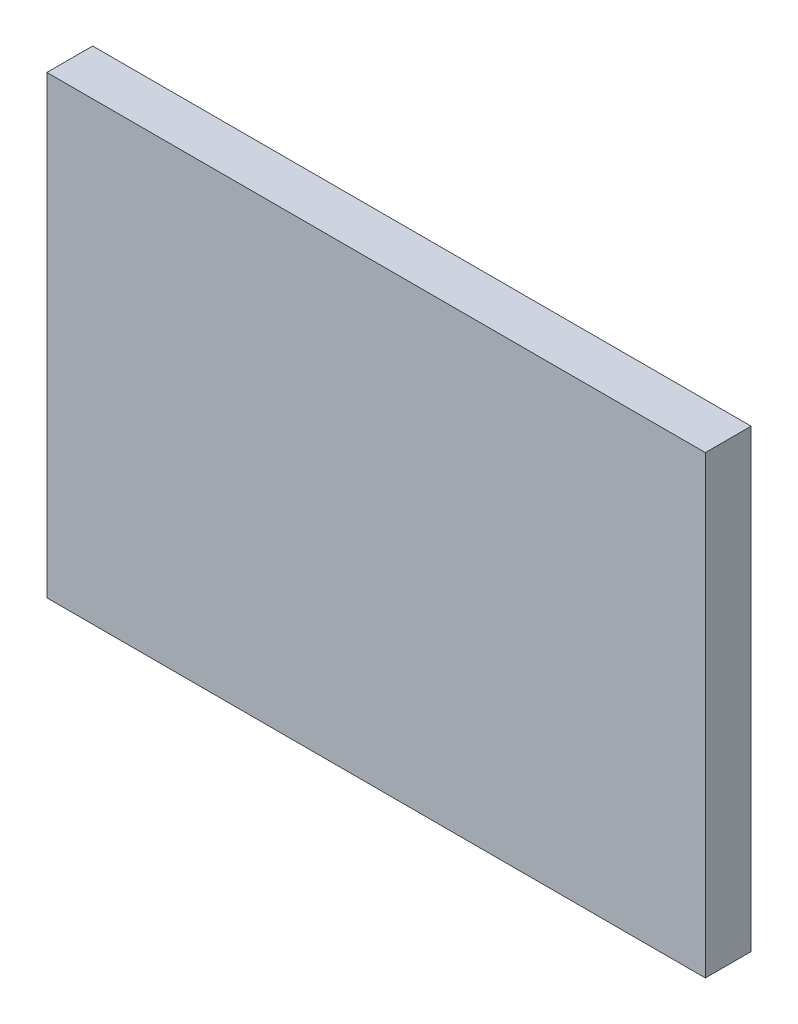
SolidWorks part; units mm, degrees
ref_plane "Front Plane" through (0, 0, 0) normal (0, 0, 1) x (1, 0, 0)
ref_plane "Top Plane" through (0, 0, 0) normal (0, 1, 0) x (1, 0, 0)
ref_plane "Right Plane" through (0, 0, 0) normal (1, 0, 0) x (0, 0, -1)
other "Configuration Table"
sketch "Sketch1" plane through (0, 0, 0) normal (0, 0, 1) x (1, 0, 0)
  line L1 (-18.7752, 18.3648) -> (17.7492, 18.3648)
  line L2 (-18.7752, 18.3648) -> (-18.7752, -6.874)
  line L3 (-18.7752, -6.874) -> (17.7492, -6.874)
  line L4 (17.7492, 18.3648) -> (17.7492, -6.874)
extrude "Boss-Extrude1" add sketch "Sketch1" along normal blind 2.54
